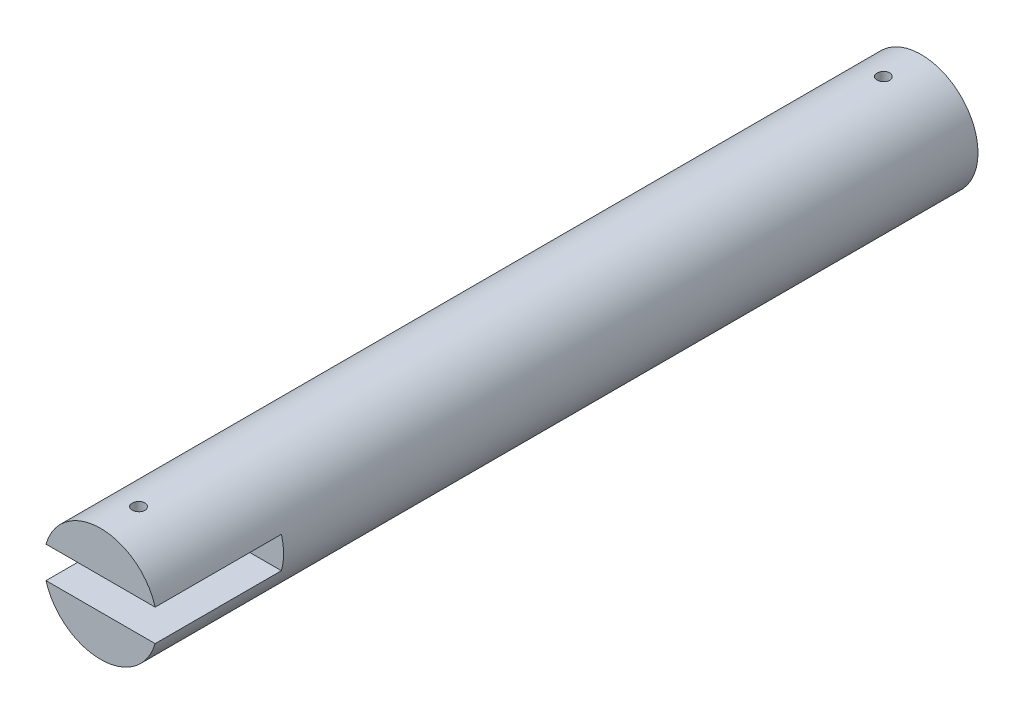
SolidWorks part; units mm, degrees
ref_plane "Płaszczyzna przednia" through (0, 0, 0) normal (0, 0, 1) x (1, 0, 0)
ref_plane "Płaszczyzna górna" through (0, 0, 0) normal (0, 1, 0) x (1, 0, 0)
ref_plane "Płaszczyzna prawa" through (0, 0, 0) normal (1, 0, 0) x (0, 0, -1)
sketch "Szkic1" plane through (0, 0, 0) normal (0, 0, 1) x (1, 0, 0)
  circle A0 centre (0, 0) radius 4.5
  dimension "D1" = 9
extrude "Dodanie-wyciągnięcie1" add sketch "Szkic1" along normal blind 65
sketch "Szkic2" plane through (0, 0, 65) normal (0, 0, 1) x (1, 0, 0)
  line L0 (-5.2571, 0) -> (6.4117, 0) construction
  line L1 (-4.3229, 1.25) -> (4.3229, 1.25)
  line L3 (-4.3229, -1.25) -> (4.3229, -1.25)
  arc A1 (-4.3229, 1.25) -> (-4.3229, -1.25) centre (0, 0) ccw
  circle A2 centre (0, 0) radius 4.5
  arc A3 (4.3229, -1.25) -> (4.3229, 1.25) centre (0, 0) ccw
  dimension "D2" = 2.5
  dimension "D1" = 0
extrude "Wytnij-wyciągnięcie1" cut sketch "Szkic2" against normal blind 10
sketch "Szkic3" plane through (0, 0, 0) normal (0, 0, -1) x (-1, 0, 0)
  circle A0 centre (0, 0) radius 2.5
  dimension "D1" = 5
extrude "Wytnij-wyciągnięcie3" cut sketch "Szkic3" against normal blind 6
sketch "Szkic4" plane through (0, 0, 0) normal (0, 1, 0) x (1, 0, 0)
  line L0 (2.5, 0) -> (-2.5, 0) construction
  circle A0 centre (0, -3) radius 0.5
  dimension "D1" = 1
  dimension "D2" = 3
extrude "Wytnij-wyciągnięcie4" cut sketch "Szkic4" along normal through all both and the other way through all
ref_plane "Płaszczyzna1" through (0, 0, 32.5) normal (0, 0, -1) x (-1, 0, 0)
mirror "Lustro1" about plane through (0, 0, 32.5) normal (0, 0, -1) of "Wytnij-wyciągnięcie4"
